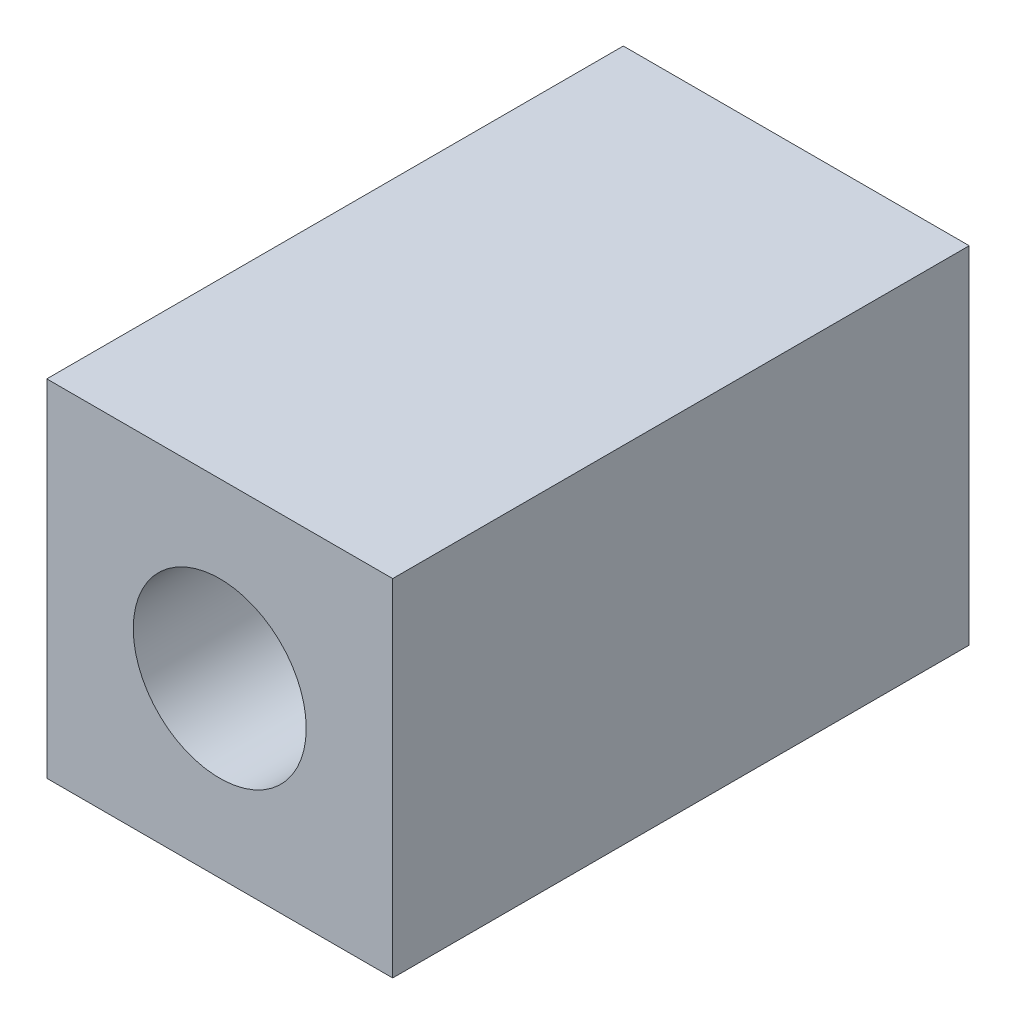
SolidWorks part; units mm, degrees
ref_plane "Front Plane" through (0, 0, 0) normal (0, 0, 1) x (1, 0, 0)
ref_plane "Top Plane" through (0, 0, 0) normal (0, 1, 0) x (1, 0, 0)
ref_plane "Right Plane" through (0, 0, 0) normal (1, 0, 0) x (0, 0, -1)
sketch "Sketch1" plane through (0, 0, 0) normal (0, 0, 1) x (1, 0, 0)
  line L1 (-7.619, 4.8889) -> (-1.619, 4.8889)
  line L2 (-7.619, 4.8889) -> (-7.619, -1.1111)
  line L3 (-7.619, -1.1111) -> (-1.619, -1.1111)
  line L4 (-1.619, 4.8889) -> (-1.619, -1.1111)
  line L5 (-7.619, 4.8889) -> (-1.619, -1.1111) construction
  line L6 (-7.619, -1.1111) -> (-1.619, 4.8889) construction
  circle A0 centre (-4.619, 1.8889) radius 1.5
  point P4 (-4.619, 1.8889)
  dimension "D1" = 6
  dimension "D2" = 6
extrude "Boss-Extrude1" add sketch "Sketch1" along normal blind 10
